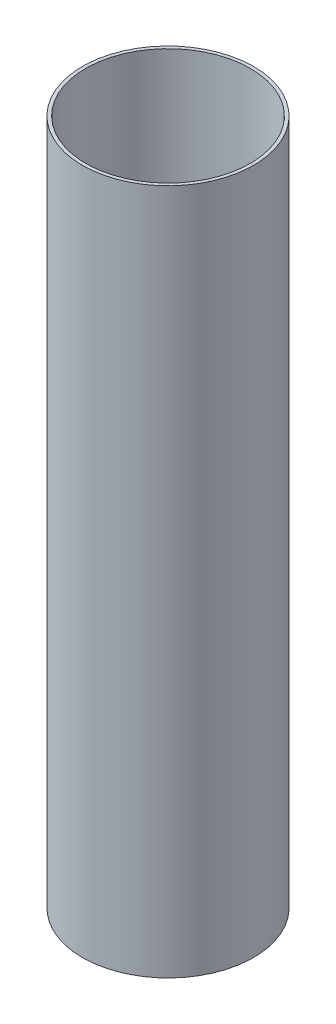
SolidWorks part; units mm, degrees
material "A-Glass Fiber"
ref_plane "Front Plane" through (0, 0, 0) normal (0, 0, 1) x (1, 0, 0)
ref_plane "Top Plane" through (0, 0, 0) normal (0, 1, 0) x (1, 0, 0)
ref_plane "Right Plane" through (0, 0, 0) normal (1, 0, 0) x (0, 0, -1)
sketch "Sketch1" plane through (0, 0, 0) normal (0, 1, 0) x (1, 0, 0)
  circle A0 centre (0, 0) radius 38.1
  circle A1 centre (0, 0) radius 39.624
  dimension "D1" = 76.2
  dimension "D2" = 79.248
extrude "Boss-Extrude1" add sketch "Sketch1" along normal blind 317.5
